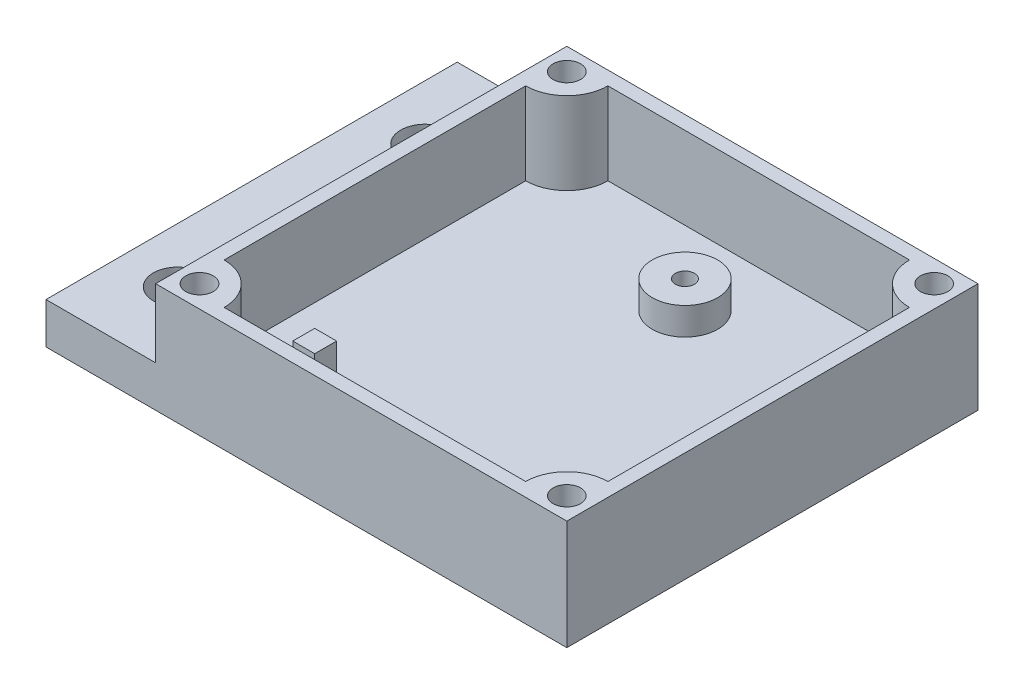
SolidWorks part; units mm, degrees
ref_plane "Front Plane" through (0, 0, 0) normal (0, 0, 1) x (1, 0, 0)
ref_plane "Top Plane" through (0, 0, 0) normal (0, 1, 0) x (1, 0, 0)
ref_plane "Right Plane" through (0, 0, 0) normal (1, 0, 0) x (0, 0, -1)
sketch "Sketch1" plane through (0, 0, 0) normal (0, 1, 0) x (1, 0, 0)
  line L1 (19.05, -19.05) -> (-19.05, -19.05)
  line L2 (19.05, -19.05) -> (19.05, 19.05)
  line L3 (19.05, 19.05) -> (-19.05, 19.05)
  line L4 (-19.05, -19.05) -> (-19.05, 19.05)
  line L5 (19.05, -19.05) -> (-19.05, 19.05) construction
  line L6 (19.05, 19.05) -> (-19.05, -19.05) construction
  point P0 (0, 0)
  dimension "D1" = 38.1
  dimension "D2" = 38.1
extrude "Boss-Extrude1" add sketch "Sketch1" along normal blind 2.54 contours L3 L4 L1 L2
sketch "Sketch2" plane through (0, 2.54, 0) normal (0, 1, 0) x (1, 0, 0)
  line L0 (-19.05, -19.05) -> (-19.05, 19.05) construction
  line L3 (15.24, 15.24) -> (14.9402, 15.24)
  line L6 (15.24, 15.24) -> (15.0859, 15.0859) construction
  line L7 (19.05, 19.05) -> (-19.05, 19.05) construction
  line L8 (0, 0) -> (0, 7.4768) construction
  line L9 (0, 7.4768) -> (0, 0) construction
  line L10 (0, 0) -> (-6.6738, 0) construction
  line L11 (19.05, -19.05) -> (-19.05, -19.05) construction
  line L13 (17.78, -13.97) -> (17.78, 13.97)
  line L15 (-17.78, 13.97) -> (-17.78, -13.97)
  line L17 (13.97, -17.78) -> (-13.97, -17.78)
  line L19 (-13.97, 17.78) -> (13.97, 17.78)
  line L22 (15.24, 14.9402) -> (15.24, 15.24)
  circle A0 centre (-17.018, 17.018) radius 1.27
  circle A1 centre (-17.018, -17.018) radius 1.27
  circle A2 centre (17.018, -17.018) radius 1.27
  circle A3 centre (17.018, 17.018) radius 1.27
  arc A4 (-17.78, 13.97) -> (-13.97, 17.78) centre (-17.78, 17.78) ccw
  arc A5 (-17.78, -13.97) -> (-13.97, -17.78) centre (-17.78, -17.78) cw
  arc A6 (17.78, -13.97) -> (13.97, -17.78) centre (17.78, -17.78) ccw
  arc A7 (17.78, 13.97) -> (13.97, 17.78) centre (17.78, 17.78) cw
  point P0 (0, 0)
  dimension "D3" = 2.54
  dimension "D2" = 3.81
  dimension "D4" = 2.032
  dimension "D5" = 2.032
  dimension "D6" = 1.27
  dimension "D8" = 5.08
  dimension "D10" = 1.27
extrude "Boss-Extrude2" add sketch "Sketch2" along normal blind 7.62
sketch "Sketch4" plane through (0, 2.54, 0) normal (0, 1, 0) x (1, 0, 0)
  line L2 (-13.1774, -12.2172) -> (-11.1454, -12.2172)
  line L3 (-13.1774, -12.2172) -> (-13.1774, -10.1852)
  line L4 (-13.1774, -10.1852) -> (-11.1454, -10.1852)
  line L5 (-11.1454, -12.2172) -> (-11.1454, -10.1852)
  line L6 (-13.1774, -12.2172) -> (-11.1454, -10.1852) construction
  line L7 (-13.1774, -10.1852) -> (-11.1454, -12.2172) construction
  line L8 (10.541, -12.2172) -> (12.573, -12.2172)
  line L9 (10.541, -12.2172) -> (10.541, -10.1852)
  line L10 (10.541, -10.1852) -> (12.573, -10.1852)
  line L11 (12.573, -12.2172) -> (12.573, -10.1852)
  line L12 (10.541, -12.2172) -> (12.573, -10.1852) construction
  line L13 (10.541, -10.1852) -> (12.573, -12.2172) construction
  line L16 (-13.97, 17.78) -> (13.97, 17.78) construction
  line L18 (14.605, -14.2492) -> (-14.605, -14.2492)
  line L19 (14.605, -14.2492) -> (14.605, 14.2492)
  line L20 (14.605, 14.2492) -> (-14.605, 14.2492)
  line L21 (-14.605, -14.2492) -> (-14.605, 14.2492)
  line L22 (14.605, -14.2492) -> (-14.605, 14.2492) construction
  line L23 (14.605, 14.2492) -> (-14.605, -14.2492) construction
  circle A0 centre (0, 10.9472) radius 3.0302
  circle A1 centre (0, 10.9472) radius 0.8831
  point P2 (-12.1614, -11.2012)
  point P10 (11.557, -11.2012)
  point P15 (0, 0)
  dimension "D1" = 6.8328
  dimension "D2" = 1.4276
  dimension "D3" = 2.032
  dimension "D4" = 2.032
  dimension "D5" = 2.032
  dimension "D6" = 2.032
  dimension "D7" = 2.032
  dimension "D8" = 2.032
  dimension "D9" = 3.302
  dimension "D10" = 29.21
extrude "Boss-Extrude3" add sketch "Sketch4" along normal blind 2.54 contours A1 | L2 L5 L4 L3 | L8 L11 L10 L9 | A0
sketch "Sketch7" plane through (0, 0, 0) normal (0, -1, 0) x (1, 0, 0)
  line L0 (19.05, -19.05) -> (-19.05, -19.05) construction
  line L1 (-29.21, 19.05) -> (-19.05, 19.05)
  line L2 (-29.21, 19.05) -> (-29.21, -19.05)
  line L3 (-29.21, -19.05) -> (-19.05, -19.05)
  line L4 (-19.05, 19.05) -> (-19.05, -19.05)
  line L5 (-29.21, 19.05) -> (-19.05, -19.05) construction
  line L6 (-29.21, -19.05) -> (-19.05, 19.05) construction
  line L7 (-19.05, 19.05) -> (-19.05, -19.05) construction
  circle A0 centre (-24.13, -10.9906) radius 2.2479
  circle A1 centre (-24.13, 11.937) radius 2.2479
  point P0 (-24.13, 0)
  point P13 (0, 0)
  point P15 (0, 0)
  point P16 (0, 0)
  point P18 (-24.0566, -9.4416)
  dimension "D1" = 4.4958
  dimension "D2" = 5.08
  dimension "D3" = 10.16
extrude "Boss-Extrude5" add sketch "Sketch7" against normal blind 3.81
